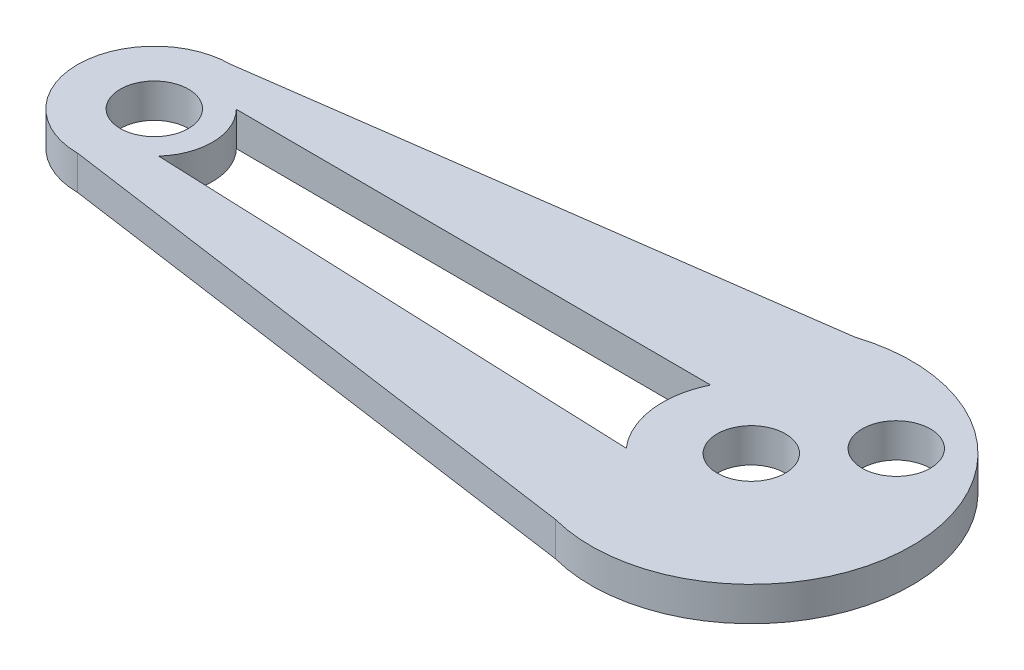
SolidWorks part; units mm, degrees
ref_plane "Front Plane" through (0, 0, 0) normal (0, 0, 1) x (1, 0, 0)
ref_plane "Top Plane" through (0, 0, 0) normal (0, 1, 0) x (1, 0, 0)
ref_plane "Right Plane" through (0, 0, 0) normal (1, 0, 0) x (0, 0, -1)
sketch "Sketch1" plane through (0, 0, 0) normal (0, 1, 0) x (1, 0, 0)
  line L0 (-51.6302, -5.0027) -> (-19.5205, -0.5581)
  line L1 (-51.6302, -14.0027) -> (-19.0302, -18.5912)
  line L2 (-51.6302, -9.5027) -> (-16.6302, -9.5027) construction
  line L3 (-49.202, -7.1228) -> (-21.302, -7.2194)
  line L4 (-49.102, -11.7762) -> (-20.5646, -12.9027)
  arc A0 (-51.6302, -5.0027) -> (-51.6302, -14.0027) centre (-51.6302, -9.5027) ccw
  circle A1 centre (-16.6302, -9.5027) radius 2
  arc A2 (-19.0302, -18.5912) -> (-19.5205, -0.5581) centre (-16.6302, -9.5027) ccw
  circle A3 centre (-51.6302, -9.5027) radius 2
  arc A4 (-49.102, -11.7762) -> (-49.202, -7.1228) centre (-51.6302, -9.5027) ccw
  arc A5 (-21.302, -7.2194) -> (-20.5646, -12.9027) centre (-16.6302, -9.5027) ccw
  circle A6 centre (-12.6302, -5.0027) radius 2
  dimension "D1" = 9
  dimension "D2" = 18.8
  dimension "D3" = 4
  dimension "D5" = 4
  dimension "D6" = 6.8
  dimension "D7" = 10.4
  dimension "D10" = 4
  dimension "D4" = 35
  dimension "D8" = 4
  dimension "D9" = 4.5
extrude "Boss-Extrude1" add sketch "Sketch1" along normal blind 2
